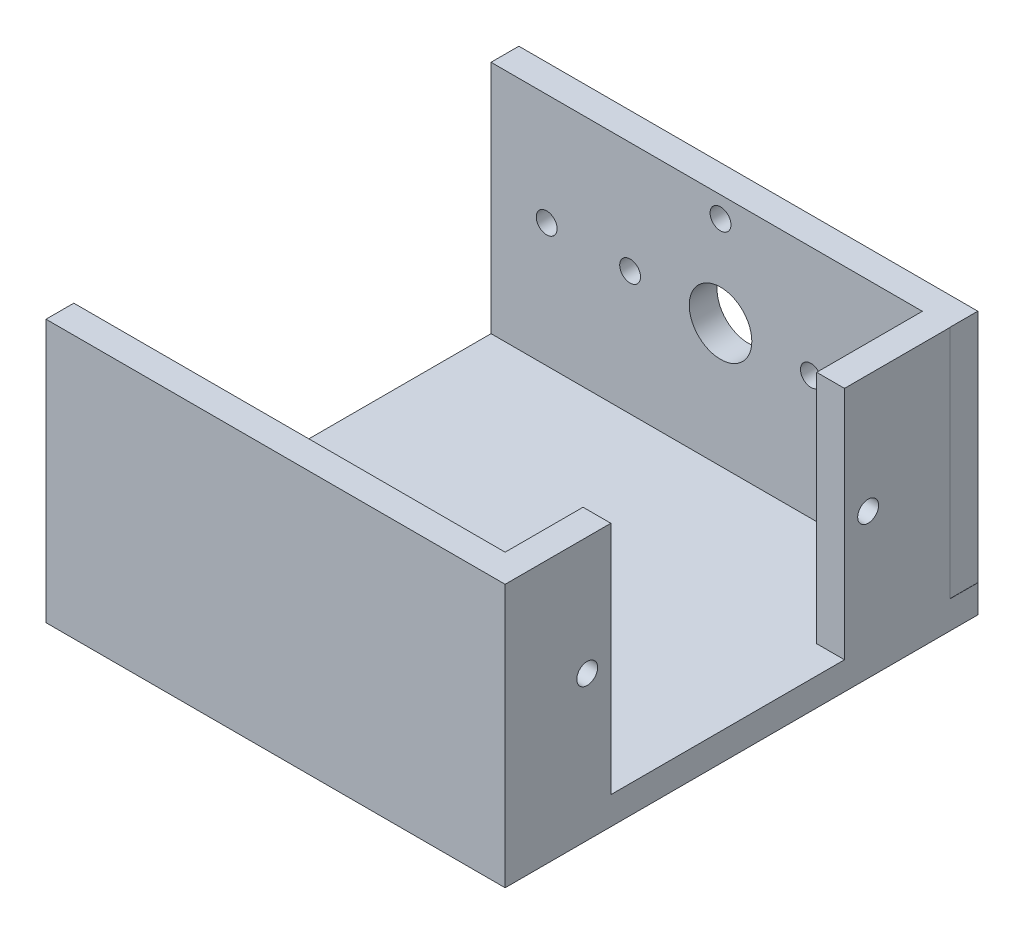
SolidWorks part; units mm, degrees
ref_plane "前视基准面" through (0, 0, 0) normal (0, 0, 1) x (1, 0, 0)
ref_plane "上视基准面" through (0, 0, 0) normal (0, 1, 0) x (1, 0, 0)
ref_plane "右视基准面" through (0, 0, 0) normal (1, 0, 0) x (0, 0, -1)
sketch "草图1" plane through (0, 0, 0) normal (0, 0, 1) x (1, 0, 0)
  line L0 (-43.3841, 0) -> (43.3841, 0) construction
  line L1 (0, 36.577) -> (0, -36.577) construction
  line L2 (-26.1516, 10.9) -> (26.1516, 10.9) construction
  line L3 (-16.5, 0) -> (16.5, 0)
  line L4 (-16.5, 0) -> (-16.5, 18.9)
  line L5 (-16.5, 18.9) -> (16.5, 18.9)
  line L6 (16.5, 0) -> (16.5, 18.9)
  circle A0 centre (0, 10.9) radius 2.25
  circle A1 centre (0, 17.4) radius 0.75
  circle A2 centre (-6.5, 10.9) radius 0.75
  circle A3 centre (-12.5, 10.9) radius 0.75
  circle A4 centre (6.5, 10.9) radius 0.75
  circle A5 centre (12.5, 10.9) radius 0.75
  point P4 (0, 0)
  point P8 (0, 0)
  point P17 (0, 10.9)
  dimension "D4" = 4.5
  dimension "D6" = 1.5
  dimension "D8" = 1.5
  dimension "D10" = 1.5
  dimension "D1" = 33
  dimension "D2" = 18.9
  dimension "D3" = 16.5
  dimension "D5" = 8
  dimension "D7" = 6.5
  dimension "D9" = 6.5
  dimension "D11" = 12.5
extrude "凸台-拉伸1" add sketch "草图1" along normal blind 2
sketch "草图3" plane through (0, 0, 0) normal (0, -1, 0) x (1, 0, 0)
  line L1 (-16.5, 0) -> (16.5142, 0)
  line L2 (-16.5, 0) -> (-16.5, 32)
  line L3 (-16.5, 32) -> (16.5142, 32)
  line L4 (16.5142, 0) -> (16.5142, 32)
  dimension "D1" = 32
extrude "凸台-拉伸2" add sketch "草图3" against normal blind 2
sketch "草图7" plane through (16.5142, 0, 0) normal (1, 0, 0) x (0, 0, -1)
  line L0 (-18, 21.9095) -> (-18, -17.9095) construction
  line L3 (-32, 2) -> (-26.4, 2)
  line L4 (-32, 2) -> (-32, 18.9)
  line L5 (-32, 18.9) -> (-26.4, 18.9)
  line L6 (-26.4, 2) -> (-26.4, 18.9)
  line L7 (-2, 2) -> (-9.6, 2)
  line L8 (-2, 2) -> (-2, 18.9)
  line L9 (-2, 18.9) -> (-9.6, 18.9)
  line L10 (-9.6, 2) -> (-9.6, 18.9)
  circle A0 centre (-7.9, 10.4) radius 0.75
  circle A1 centre (-28.1, 10.4) radius 0.75
  point P3 (-18, 2)
  dimension "D6" = 1.5
  dimension "D1" = 16.9
  dimension "D2" = 16.9
  dimension "D3" = 8.4
  dimension "D4" = 8.4
  dimension "D5" = 5.6
  dimension "D7" = 8.5
  dimension "D8" = 1.7
extrude "凸台-拉伸3" add sketch "草图7" against normal blind 2
sketch "草图8" plane through (0, 0, 32) normal (0, 0, 1) x (1, 0, 0)
  line L1 (16.5142, 0) -> (-16.5, 0)
  line L2 (16.5142, 0) -> (16.5142, 18.9)
  line L3 (16.5142, 18.9) -> (-16.5, 18.9)
  line L4 (-16.5, 0) -> (-16.5, 18.9)
extrude "凸台-拉伸4" add sketch "草图8" along normal blind 2
